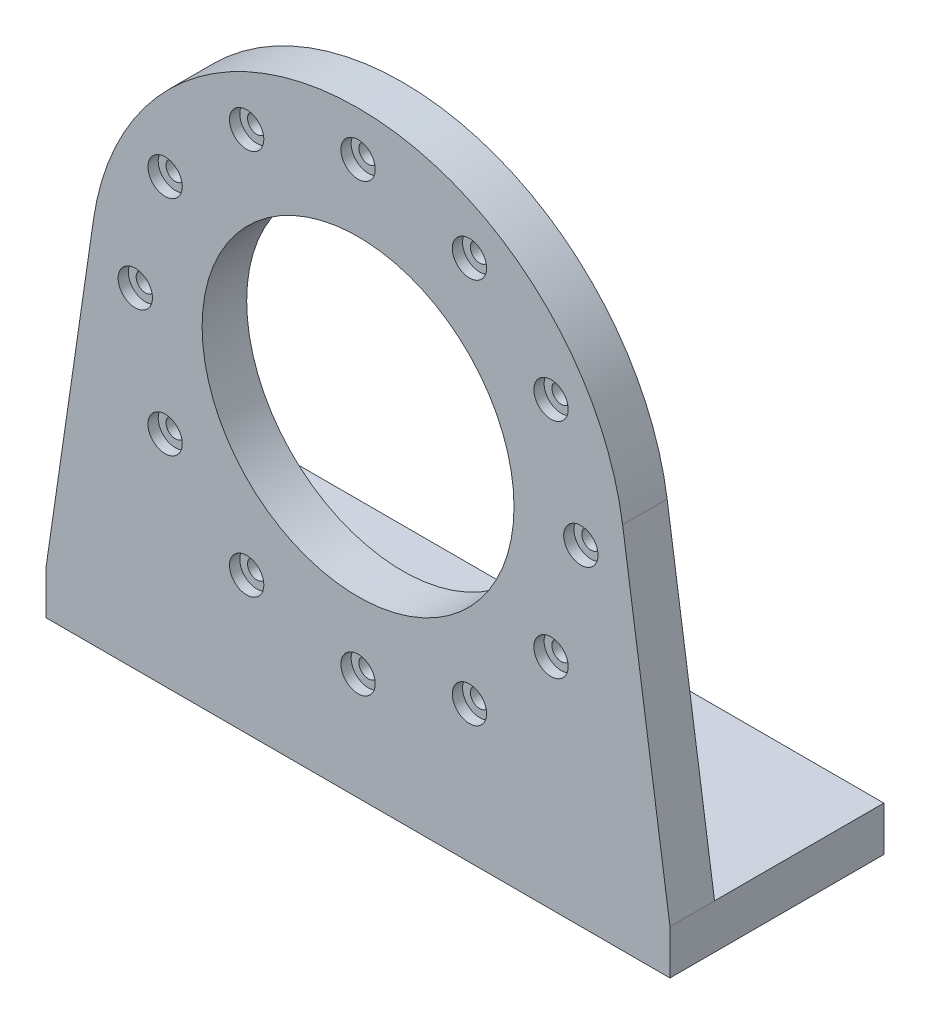
SolidWorks part; units mm, degrees
material "ABS"
ref_plane "Front Plane" through (0, 0, 0) normal (0, 0, 1) x (1, 0, 0)
ref_plane "Top Plane" through (0, 0, 0) normal (0, 1, 0) x (1, 0, 0)
ref_plane "Right Plane" through (0, 0, 0) normal (1, 0, 0) x (0, 0, -1)
sketch "Sketch1" plane through (0, 0, 0) normal (0, 0, 1) x (1, 0, 0)
  line L0 (0, 0) -> (-50, 0) construction
  line L1 (0, 0) -> (0, -64.1) construction
  line L2 (0, -64.1) -> (-70, -64.1)
  line L3 (0, -64.1) -> (70, -64.1)
  line L4 (-70, -64.1) -> (-59.3699, 8.6723)
  line L5 (70, -64.1) -> (59.3699, 8.6723)
  arc A0 (59.3699, 8.6723) -> (-59.3699, 8.6723) centre (0, 0) ccw
  circle A1 centre (0, 0) radius 35
  circle A2 centre (-50, 0) radius 2.1
  circle A3 centre (-43.3013, 25) radius 2.1
  circle A4 centre (-25, 43.3013) radius 2.1
  circle A5 centre (0, 50) radius 2.1
  circle A6 centre (25, 43.3013) radius 2.1
  circle A7 centre (43.3013, 25) radius 2.1
  circle A8 centre (50, 0) radius 2.1
  circle A9 centre (43.3013, -25) radius 2.1
  circle A10 centre (25, -43.3013) radius 2.1
  circle A11 centre (0, -50) radius 2.1
  circle A12 centre (-25, -43.3013) radius 2.1
  circle A13 centre (-43.3013, -25) radius 2.1
  arc A14 (-59.3699, 8.6723) -> (0, -60) centre (0, 0) ccw construction
  arc A15 (0, -60) -> (59.3699, 8.6723) centre (0, 0) ccw construction
  point P30 (0, 0)
  dimension "D1" = 120
  dimension "D2" = 70
  dimension "D3" = 50
  dimension "D4" = 4.2
  dimension "D5" = 12
  dimension "D6" = 64.1
  dimension "D7" = 70
extrude "Boss-Extrude1" add sketch "Sketch1" along normal blind 10
sketch "Sketch2" plane through (0, 0, 10) normal (0, 0, 1) x (1, 0, 0)
  line L1 (-70, -64.1) -> (70, -64.1)
  line L2 (-70, -64.1) -> (-70, -74.1)
  line L3 (-70, -74.1) -> (70, -74.1)
  line L4 (70, -64.1) -> (70, -74.1)
  dimension "D1" = 10
extrude "Boss-Extrude2" add sketch "Sketch2" against normal blind 48
sketch "Sketch3" plane through (0, 0, 10) normal (0, 0, 1) x (1, 0, 0)
  circle A0 centre (0, -50) radius 3.85
  circle A1 centre (-25, -43.3013) radius 3.85
  circle A2 centre (-43.3013, -25) radius 3.85
  circle A3 centre (-50, 0) radius 3.85
  circle A4 centre (-43.3013, 25) radius 3.85
  circle A5 centre (-25, 43.3013) radius 3.85
  circle A6 centre (0, 50) radius 3.85
  circle A7 centre (25, 43.3013) radius 3.85
  circle A8 centre (43.3013, 25) radius 3.85
  circle A9 centre (50, 0) radius 3.85
  circle A10 centre (43.3013, -25) radius 3.85
  circle A11 centre (25, -43.3013) radius 3.85
  point P27 (0, 0)
  dimension "D1" = 7.7
  dimension "D2" = 12
extrude "Cut-Extrude1" cut sketch "Sketch3" against normal blind 2.3
